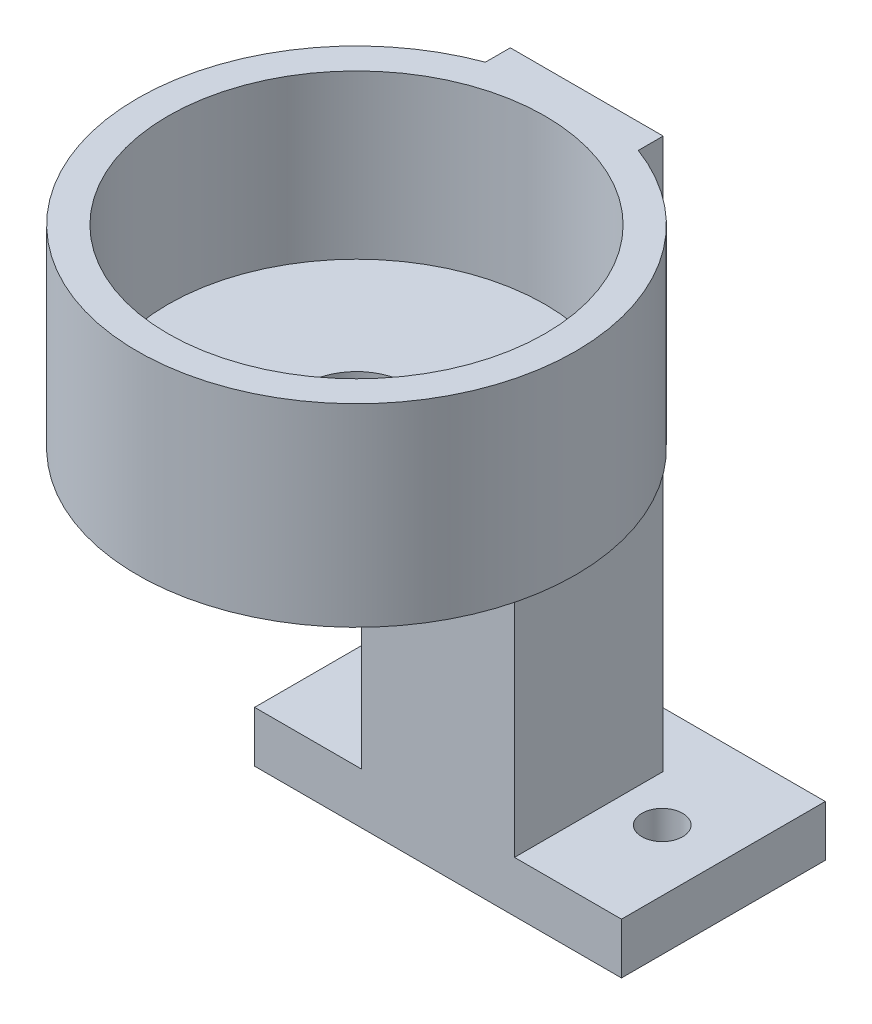
SolidWorks part; units mm, degrees
ref_plane "Plan de face" through (0, 0, 0) normal (0, 0, 1) x (1, 0, 0)
ref_plane "Plan de dessus" through (0, 0, 0) normal (0, 1, 0) x (1, 0, 0)
ref_plane "Plan de droite" through (0, 0, 0) normal (1, 0, 0) x (0, 0, -1)
sketch "Esquisse1" plane through (0, 0, 0) normal (0, 1, 0) x (1, 0, 0)
  line L1 (0, 0) -> (36, 0)
  line L2 (0, 0) -> (0, 20)
  line L3 (0, 20) -> (36, 20)
  line L4 (36, 0) -> (36, 20)
  dimension "D1" = 36
  dimension "D2" = 20
extrude "Boss.-Extru.1" add sketch "Esquisse1" along normal blind 5
sketch "Esquisse2" plane through (0, 5, 0) normal (0, 1, 0) x (1, 0, 0)
  line L0 (0, 0) -> (36, 0) construction
  line L1 (10.5, 0) -> (25.5, 0)
  line L2 (10.5, 0) -> (10.5, 10.5912)
  line L3 (10.5, 10.5912) -> (25.5, 10.5912)
  line L4 (25.5, 0) -> (25.5, 10.5912)
  line L5 (0, 20) -> (0, 0) construction
  line L7 (10.5, 10.5912) -> (25.5, 10.5912)
  line L8 (10.5, 10.5912) -> (10.5, 14.5912)
  line L9 (10.5, 14.5912) -> (25.5, 14.5912)
  line L10 (25.5, 10.5912) -> (25.5, 14.5912)
  dimension "D1" = 15
  dimension "D2" = 10.5
  dimension "D3" = 4
extrude "Boss.-Extru.2" add sketch "Esquisse2" along normal blind 32 contours L2 L1 L4 L3 | L8 L7 L10 L9
sketch "Esquisse3" plane through (0, 37, 0) normal (0, 1, 0) x (1, 0, 0)
  line L1 (10.5, 0) -> (25.5, 0)
  line L2 (10.5, 0) -> (10.5, -15.5)
  line L3 (10.5, -15.5) -> (25.5, -15.5)
  line L4 (25.5, 0) -> (25.5, -15.5)
  circle A0 centre (18, -8) radius 5
  circle A1 centre (18, -8) radius 7.5
  circle A2 centre (18, -8) radius 7.5
  dimension "D2" = 10
  dimension "D3" = 8
  dimension "D1" = 15
  dimension "D4" = 15.5
  dimension "D5" = 7.5
extrude "Boss.-Extru.3" add sketch "Esquisse3" along normal blind 6
sketch "Esquisse4" plane through (0, 43, 0) normal (0, 1, 0) x (1, 0, 0)
  circle A0 centre (18, -8) radius 18.5
  circle A1 centre (18, -8) radius 21.5
  circle A2 centre (18, -8) radius 5
extrude "Boss.-Extru.4" add sketch "Esquisse4" along normal blind 16
sketch "Esquisse5" plane through (0, 43, 0) normal (0, 1, 0) x (1, 0, 0)
  circle A0 centre (18, -8) radius 7.5
  circle A1 centre (18, -8) radius 21.5
extrude "Boss.-Extru.5" add sketch "Esquisse5" against normal blind 3
sketch "Esquisse6" plane through (0, 43, 0) normal (0, 1, 0) x (1, 0, 0)
  line L1 (10.5, 14.5912) -> (25.5, 14.5912)
  line L2 (10.5, 14.5912) -> (10.5, 11.178)
  line L3 (10.5, 11.178) -> (25.5, 11.178)
  line L4 (25.5, 14.5912) -> (25.5, 11.178)
extrude "Boss.-Extru.6" add sketch "Esquisse6" along normal blind 16
sketch "Esquisse8" plane through (0, 0, 0) normal (0, -1, 0) x (1, 0, 0)
  line L0 (0, -20) -> (0, 0) construction
  line L1 (36, 0) -> (36, -20) construction
  line L2 (36, -20) -> (0, -20) construction
  circle A0 centre (6, -10) radius 2
  circle A1 centre (30, -10) radius 2
  dimension "D1" = 4
  dimension "D2" = 4
  dimension "D3" = 6
  dimension "D4" = 6
  dimension "D5" = 10
  dimension "D6" = 10
extrude "Enlèv. mat.-Extru.1" cut sketch "Esquisse8" against normal blind 16
